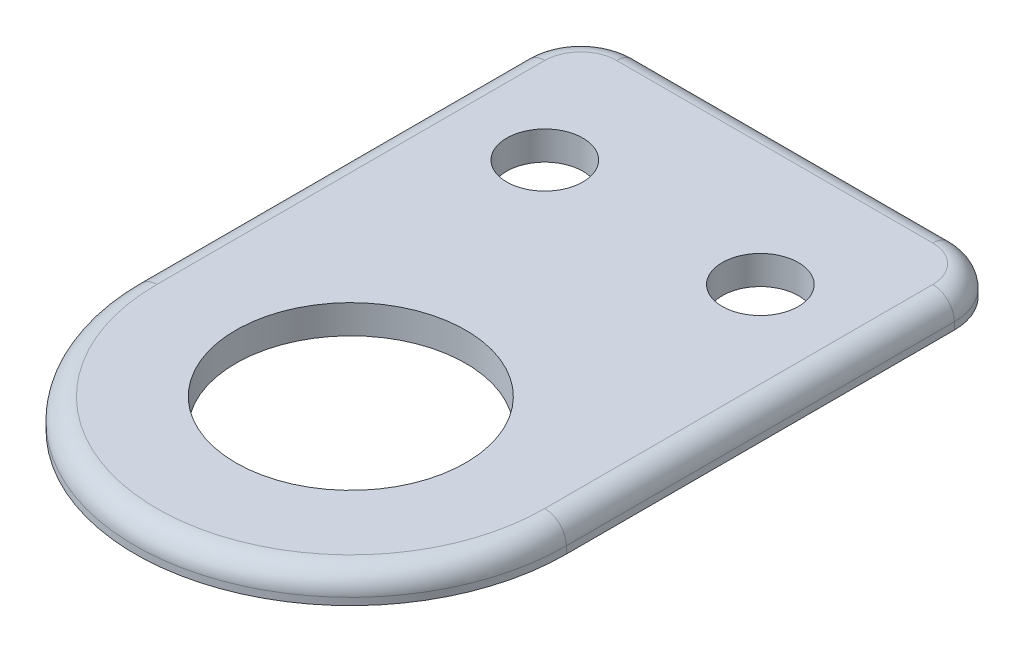
SolidWorks part; units mm, degrees
ref_plane "Front Plane" through (0, 0, 0) normal (0, 0, 1) x (1, 0, 0)
ref_plane "Top Plane" through (0, 0, 0) normal (0, 1, 0) x (1, 0, 0)
ref_plane "Right Plane" through (0, 0, 0) normal (1, 0, 0) x (0, 0, -1)
sketch "Sketch1" plane through (0, 0, 0) normal (0, 1, 0) x (1, 0, 0)
  line L0 (-15, 0) -> (15, 0)
  line L1 (-15, 0) -> (-15, 31)
  line L2 (-15, 31) -> (15, 31)
  line L3 (15, 0) -> (15, 31)
  circle A0 centre (0, 0) radius 11
  arc A1 (15, 0) -> (-15, 0) centre (0, 0) cw
  circle A2 centre (0, 0) radius 8
  point P7 (11, 0)
  point P8 (-11, 0)
  point P9 (0, 11)
  dimension "D1" = 22
  dimension "D4" = 16
  dimension "D2" = 31
  dimension "D3" = 30
extrude "Boss-Extrude1" add sketch "Sketch1" along normal blind 2 contours A0 L0 L3 L2 L1 | A2 L0 A0 | L0 A2 | L0 A2 | A2 L0 A0 | A1 L0 A0
hole_wizard "M5 Clearance Hole1" positions "3DSketch1" profile "Sketch2" hole size "M5" standard "ANSI Metric" end condition through all
sketch3d "3DSketch1"
  line L0 (-15, 2, 0) -> (-15, 2, -31) construction
  line L1 (15, 2, 0) -> (15, 2, -31) construction
  line L2 (-7.5, 2, -21) -> (7.5, 2, -21)
  line L3 (-15, 2, -31) -> (15, 2, -31) construction
  point P0 (-7.5, 2, -21)
  point P2 (7.5, 2, -21)
  dimension "D1" = 7.5
  dimension "D2" = 7.5
  dimension "D3" = 10
sketch "Sketch2" plane through (-7.5, 2, -21) normal (1, 0, 0) x (0, 0, 1)
  line L0 (0, 0) -> (0, 2)
  line L1 (0, 2) -> (2.65, 2)
  line L2 (2.65, 2) -> (2.65, 0)
  line L5 (2.65, 0) -> (0, 0)
  line L11 (0, -6.35) -> (0, 107.95) construction
  dimension "Thru Hole Dia." = 5.3
  dimension "Thru Hole Depth" = 2
fillet "Fillet1" radius 4 2 edges at (15, 1, -31) (-15, 1, -31)
fillet "Fillet2" radius 1.5 6 edges at (15, 2, -13.5) (13.8284, 2, -29.8284) (0, 2, -31) (-13.8284, 2, -29.8284) (-15, 2, -13.5) (0, 2, 15)
